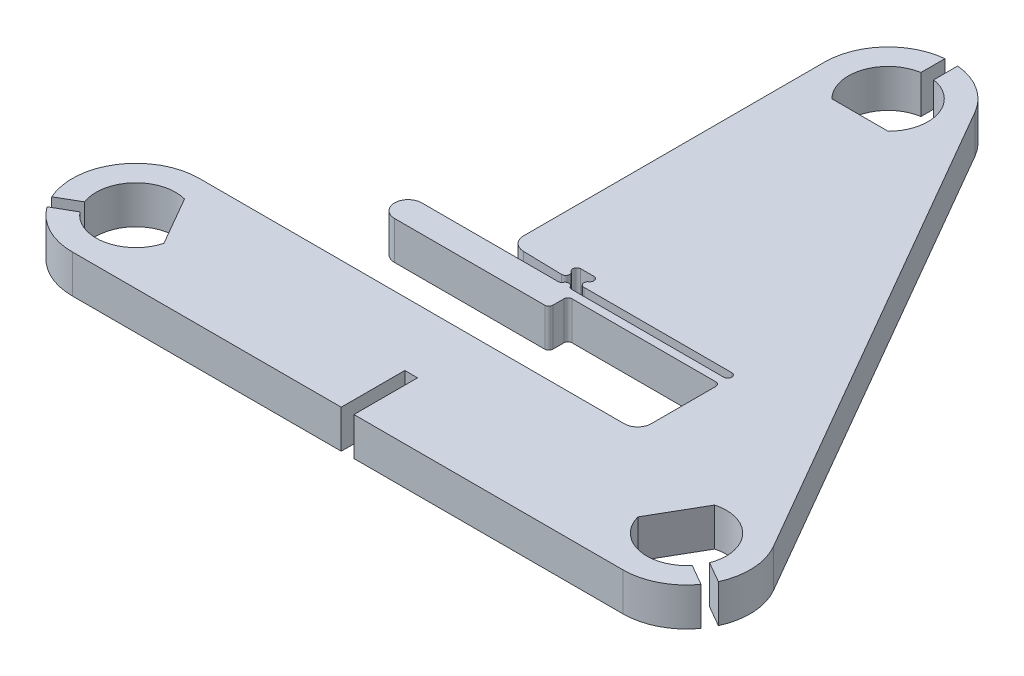
SolidWorks part; units mm, degrees
ref_plane "Front Plane" through (0, 0, 0) normal (0, 0, 1) x (1, 0, 0)
ref_plane "Top Plane" through (0, 0, 0) normal (0, 1, 0) x (1, 0, 0)
ref_plane "Right Plane" through (0, 0, 0) normal (1, 0, 0) x (0, 0, -1)
sketch "Sketch1" plane through (0, 0, 0) normal (0, 1, 0) x (1, 0, 0)
  line L0 (0, -0.565) -> (0, 0.565) construction
  line L1 (-0.5, -0.565) -> (0.5, -0.565) construction
  line L2 (0.5, -0.565) -> (0.44, 0.565) construction
  line L3 (0.44, 0.565) -> (-0.44, 0.565) construction
  line L4 (-0.5, -0.565) -> (-0.44, 0.565) construction
  line L5 (0, 0) -> (0, 20) construction
  line L6 (-1.7678, 18.2322) -> (1.7678, 18.2322)
  line L7 (1.7678, 18.2322) -> (0, 20) construction
  line L8 (0, 20) -> (-1.7678, 18.2322) construction
  line L9 (16.6735, -7.5852) -> (14.9057, -10.647)
  line L10 (-14.9057, -10.647) -> (-16.6735, -7.5852)
  line L11 (-0.6983, 0.415) -> (0.6983, 0.415) construction
  line L12 (-0.4129, 1.0755) -> (0.4129, 1.0755)
  line L13 (0.6983, 0.165) -> (10, 0.165)
  line L14 (10, -0.335) -> (0.433, -0.335)
  line L15 (-0.433, -0.335) -> (-9, -0.335)
  line L16 (-4, 1.0755) -> (-4, 20)
  line L17 (-0.4, 23.9799) -> (-0.4, 22.4678)
  line L18 (0.4, 22.4678) -> (0.4, 23.9799)
  line L19 (-0.4, 23.2239) -> (0.4, 23.2239) construction
  line L20 (3.4641, 22) -> (20.7846, -8)
  line L21 (20.9672, -11.6436) -> (19.6577, -10.8875)
  line L22 (19.2577, -11.5803) -> (20.5672, -12.3364)
  line L23 (19.9125, -11.9583) -> (20.3125, -11.2655) construction
  line L24 (17.3205, -14) -> (0.4, -14)
  line L25 (0.4, -14) -> (0.4, -10)
  line L26 (0.4, -10) -> (-0.4, -10)
  line L27 (-0.4, -10) -> (-0.4, -14)
  line L28 (-0.4, -14) -> (-17.3205, -14)
  line L29 (-0.7042, 0.1651) -> (-3.1668, 0.2226)
  line L30 (-9, -2.0413) -> (0.4483, -2.0413)
  line L31 (0.6983, -1.7913) -> (0.6983, -1.085)
  line L32 (0.9483, -0.835) -> (10, -0.835)
  line L33 (10.25, -1.085) -> (10.25, -5.1468)
  line L34 (9.3968, -6) -> (-17.3205, -6)
  line L35 (20.1125, -11.6119) -> (17.3205, -10) construction
  line L36 (-17.3205, -10) -> (-15.1554, -8.75) construction
  line L38 (-19.6577, -10.8875) -> (-20.9672, -11.6436)
  line L40 (-19.2577, -11.5803) -> (-20.5672, -12.3364)
  circle A0 centre (0, 0) radius 27.5 construction
  circle A1 centre (0, 0) radius 20 construction
  arc A2 (1.7678, 18.2322) -> (0.4, 22.4678) centre (0, 20) ccw
  arc A3 (14.9057, -10.647) -> (19.2577, -11.5803) centre (17.3205, -10) ccw
  arc A4 (-16.6735, -7.5852) -> (-14.9057, -10.647) centre (-17.3205, -10) ccw construction
  arc A5 (-0.7042, 0.1651) -> (-0.5556, 0.6203) centre (-0.6983, 0.415) ccw
  arc A6 (-0.5556, 0.6203) -> (-0.4129, 1.0755) centre (-0.4129, 0.8255) cw
  arc A7 (0.4129, 1.0755) -> (0.5556, 0.6203) centre (0.4129, 0.8255) cw
  arc A8 (0.5556, 0.6203) -> (0.6983, 0.165) centre (0.6983, 0.415) ccw
  arc A9 (10, 0.165) -> (10, -0.335) centre (10, -0.085) cw
  arc A10 (0.433, -0.335) -> (0.2165, -0.21) centre (0.433, -0.085) cw
  arc A11 (0.2165, -0.21) -> (-0.2165, -0.21) centre (0, -0.335) ccw
  arc A12 (-0.2165, -0.21) -> (-0.433, -0.335) centre (-0.433, -0.085) cw
  arc A13 (-3.1668, 0.2226) -> (-4, 1.0755) centre (-3.1468, 1.0755) cw
  arc A14 (-4, 20) -> (-0.4, 23.9799) centre (0, 20) cw
  arc A15 (-0.4, 22.4678) -> (-1.7678, 18.2322) centre (0, 20) ccw
  arc A16 (0.4, 23.9799) -> (3.4641, 22) centre (0, 20) cw
  arc A17 (20.7846, -8) -> (20.9672, -11.6436) centre (17.3205, -10) cw
  arc A18 (19.6577, -10.8875) -> (16.6735, -7.5852) centre (17.3205, -10) ccw
  arc A19 (20.5672, -12.3364) -> (17.3205, -14) centre (17.3205, -10) cw
  arc A20 (-17.3205, -14) -> (-17.3205, -6) centre (-17.3205, -10) cw construction
  arc A21 (-9, -0.335) -> (-9, -2.0413) centre (-9, -1.1882) ccw
  arc A22 (0.4483, -2.0413) -> (0.6983, -1.7913) centre (0.4483, -1.7913) ccw
  arc A23 (0.6983, -1.085) -> (0.9483, -0.835) centre (0.9483, -1.085) cw
  arc A24 (10, -0.835) -> (10.25, -1.085) centre (10, -1.085) cw
  arc A25 (10.25, -5.1468) -> (9.3968, -6) centre (9.3968, -5.1468) cw
  arc A26 (-14.9057, -10.647) -> (-19.2577, -11.5803) centre (-17.3205, -10) cw
  arc A27 (-19.6577, -10.8875) -> (-16.6735, -7.5852) centre (-17.3205, -10) cw
  arc A28 (-17.3205, -14) -> (-20.5672, -12.3364) centre (-17.3205, -10) cw
  arc A29 (-20.9672, -11.6436) -> (-17.3205, -6) centre (-17.3205, -10) cw
  point P19 (-17.3205, -6)
  point P22 (0, 0)
  point P86 (-20.5672, -12.3364)
  point P88 (-20.9672, -11.6119)
  point P91 (0, 0)
  point P92 (0, 0)
  point P93 (-17.3205, -14)
  point P94 (-20.5672, -12.3364)
  point P95 (0, 0)
  point P96 (-17.3205, -6)
  point P97 (-20.9672, -11.6436)
  point P98 (-17.3205, -10)
  dimension "D4" = 55
  dimension "D5" = 40
  dimension "D6" = 2.5
  dimension "D9" = 0.25
  dimension "D11" = 4
  dimension "D15" = 0.8
  dimension "D1" = 1.13
  dimension "D2" = 0.44
  dimension "D3" = 0.5
  dimension "D8" = 0.15
  dimension "D10" = 10
  dimension "D12" = 0.8
  dimension "D13" = 5
  dimension "D14" = 0.5
  dimension "D16" = 0.4
  dimension "D7" = 3
extrude "Boss-Extrude1" add sketch "Sketch1" along normal blind 2.4
